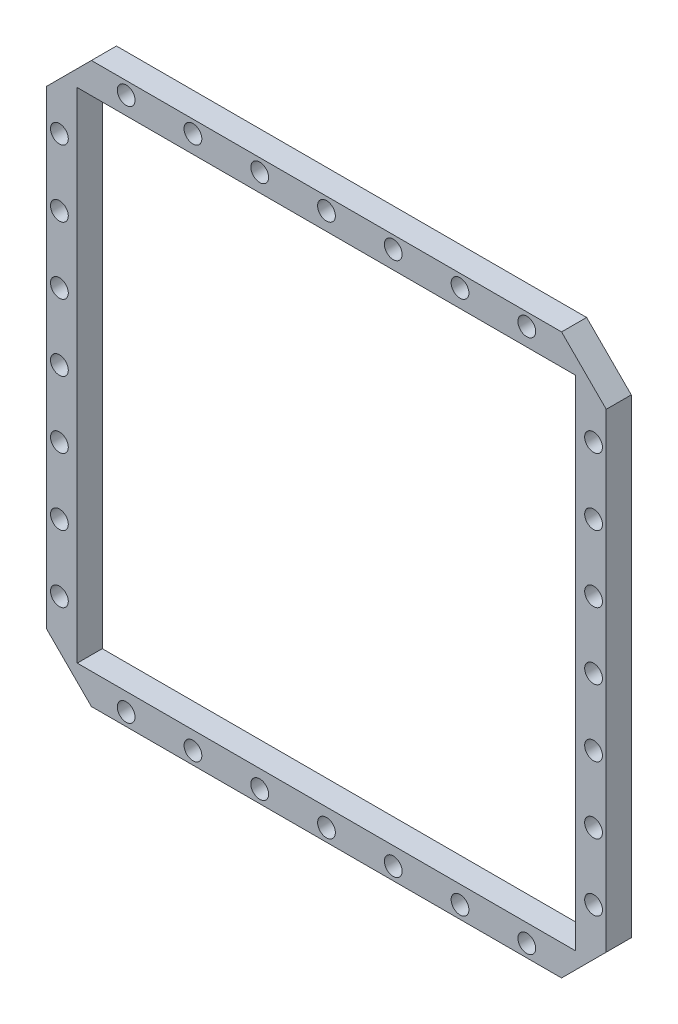
SolidWorks part; units mm, degrees
ref_plane "Front Plane" through (0, 0, 0) normal (0, 0, 1) x (1, 0, 0)
ref_plane "Top Plane" through (0, 0, 0) normal (0, 1, 0) x (1, 0, 0)
ref_plane "Right Plane" through (0, 0, 0) normal (1, 0, 0) x (0, 0, -1)
sketch "Sketch1" plane through (0, 0, 0) normal (0, 0, 1) x (1, 0, 0)
  line L0 (106.426, 0) -> (106.426, -212.852) construction
  line L1 (11.6134, -11.6134) -> (201.2386, -11.6134)
  line L2 (11.6134, -11.6134) -> (11.6134, -201.2386)
  line L3 (11.6134, -201.2386) -> (201.2386, -201.2386)
  line L4 (201.2386, -11.6134) -> (201.2386, -201.2386)
  line L5 (0, -106.426) -> (212.852, -106.426) construction
  line L6 (0, -16.9978) -> (16.9978, 0)
  line L7 (0, 0) -> (212.852, 0)
  line L8 (0, 0) -> (0, -212.852)
  line L9 (0, -212.852) -> (212.852, -212.852)
  line L10 (212.852, 0) -> (212.852, -212.852)
  line L11 (195.8542, 0) -> (212.852, -16.9978)
  line L12 (212.852, -195.8542) -> (195.8542, -212.852)
  line L13 (16.9978, -212.852) -> (0, -195.8542)
  circle A1 centre (30.226, -4.826) radius 3.38
  circle A2 centre (55.626, -4.826) radius 3.38
  circle A3 centre (81.026, -4.826) radius 3.38
  circle A4 centre (106.426, -4.826) radius 3.38
  circle A5 centre (131.826, -4.826) radius 3.38
  circle A6 centre (157.226, -4.826) radius 3.38
  circle A7 centre (182.626, -4.826) radius 3.38
  circle A8 centre (208.026, -30.226) radius 3.38
  circle A9 centre (208.026, -55.626) radius 3.38
  circle A10 centre (208.026, -81.026) radius 3.38
  circle A11 centre (208.026, -106.426) radius 3.38
  circle A12 centre (208.026, -182.626) radius 3.38
  circle A13 centre (208.026, -157.226) radius 3.38
  circle A14 centre (208.026, -131.826) radius 3.38
  circle A15 centre (182.626, -208.026) radius 3.38
  circle A16 centre (157.226, -208.026) radius 3.38
  circle A17 centre (131.826, -208.026) radius 3.38
  circle A18 centre (106.426, -208.026) radius 3.38
  circle A19 centre (30.226, -208.026) radius 3.38
  circle A20 centre (55.626, -208.026) radius 3.38
  circle A21 centre (81.026, -208.026) radius 3.38
  circle A22 centre (4.826, -182.626) radius 3.38
  circle A23 centre (4.826, -157.226) radius 3.38
  circle A24 centre (4.826, -131.826) radius 3.38
  circle A25 centre (4.826, -106.426) radius 3.38
  circle A26 centre (4.826, -30.226) radius 3.38
  circle A27 centre (4.826, -55.626) radius 3.38
  circle A28 centre (4.826, -81.026) radius 3.38
  point P5 (106.426, 0)
  point P6 (106.426, -11.6134)
  point P7 (0, -106.426)
  point P12 (11.6134, -106.426)
  point P33 (106.426, -106.426)
  point P34 (0, 0)
  point P35 (0, 0)
  point P36 (0, 0)
  point P85 (106.426, -106.426)
  point P86 (0, 0)
  dimension "D4" = 6.76
  dimension "D1" = 212.852
  dimension "D2" = 189.6252
  dimension "D3" = 45
  dimension "D5" = 7
  dimension "D6" = 25.4
  dimension "D7" = 12.0193
  dimension "D8" = 30.226
  dimension "D9" = 4.826
  dimension "D11" = 25.4
  dimension "D10" = 4
extrude "Boss-Extrude1" add sketch "Sketch1" along normal blind 9.525 contours L13 L9 L12 L10 L11 L7 L6 L8 A28 A27 A26 A25 A24 A23 A22 A21 A20 A19 A18 A17 A16 A15 A14 A13 A12 A11 A10 A9 A8
